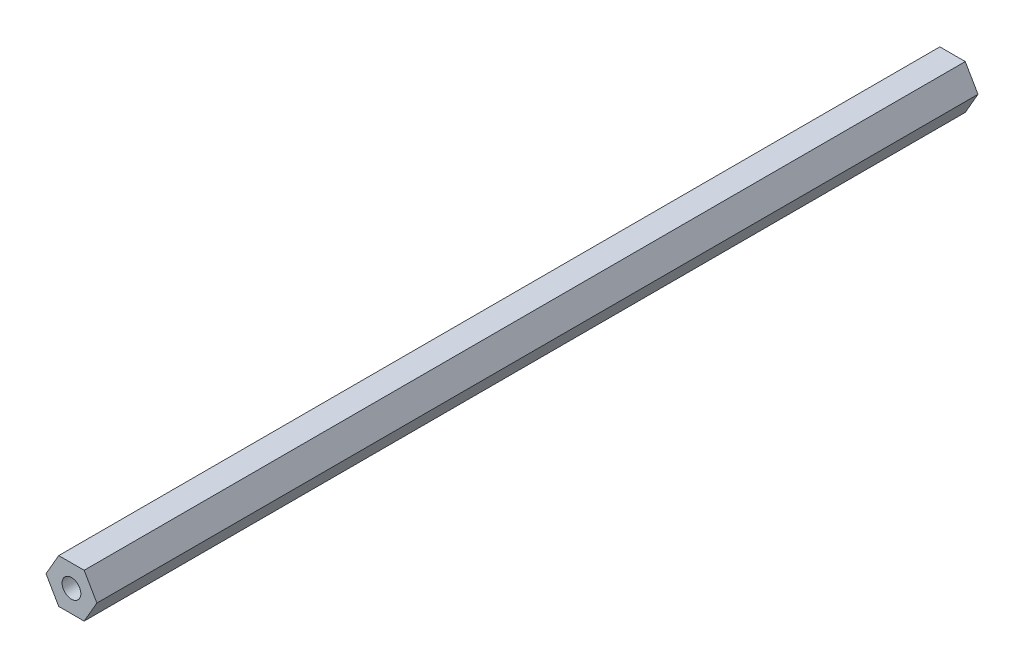
SolidWorks part; units mm, degrees
material "6061 Alloy"
ref_plane "Front Plane" through (0, 0, 0) normal (0, 0, 1) x (1, 0, 0)
ref_plane "Top Plane" through (0, 0, 0) normal (0, 1, 0) x (1, 0, 0)
ref_plane "Right Plane" through (0, 0, 0) normal (1, 0, 0) x (0, 0, -1)
sketch "Sketch1" plane through (0, 0, 0) normal (0, 0, 1) x (1, 0, 0)
  line L1 (7.3323, 0) -> (3.6662, 6.35)
  line L2 (3.6662, 6.35) -> (-3.6662, 6.35)
  line L3 (-3.6662, 6.35) -> (-7.3323, 0)
  line L4 (-7.3323, 0) -> (-3.6662, -6.35)
  line L5 (-3.6662, -6.35) -> (3.6662, -6.35)
  line L6 (3.6662, -6.35) -> (7.3323, 0)
  circle A0 centre (0, 0) radius 6.35 construction
  dimension "D1" = 12.7
extrude "Boss-Extrude1" add sketch "Sketch1" along normal mid plane 254
hole_wizard "1/4-28 Tapped Hole1" positions "3DSketch1" profile "Sketch2" tap size "1/4-28" standard "ANSI Inch"
sketch3d "3DSketch1"
  point P0 (0, 0, 127)
  point P2 (0, 0, -127)
sketch "Sketch2" plane through (0, 0, 127) normal (1, 0, 0) x (0, -1, 0)
  line L0 (0, 0) -> (0, 29.8194)
  line L1 (0, 29.8194) -> (2.7051, 28.194)
  line L2 (2.7051, 28.194) -> (2.7051, 0)
  line L5 (2.7051, 0) -> (0, 0)
  line L10 (0, 29.8194) -> (-2.7051, 28.194) construction
  line L11 (0, -6.35) -> (0, 107.95) construction
  dimension "Tap Drill Dia." = 5.4102
  dimension "Tap Drill Depth" = 28.194
  dimension "Drill Angle" = 118
